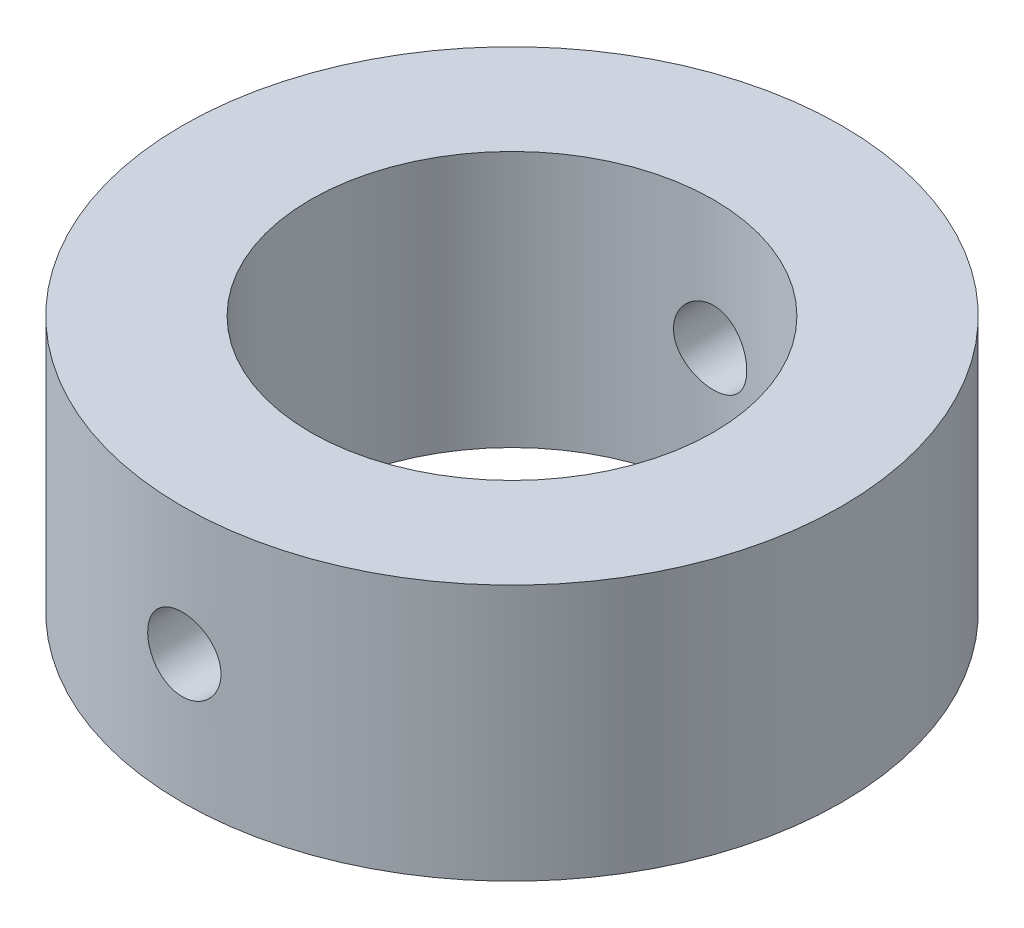
SolidWorks part; units mm, degrees
ref_plane "Front Plane" through (0, 0, 0) normal (0, 0, 1) x (1, 0, 0)
ref_plane "Top Plane" through (0, 0, 0) normal (0, 1, 0) x (1, 0, 0)
ref_plane "Right Plane" through (0, 0, 0) normal (1, 0, 0) x (0, 0, -1)
sketch "Sketch2" plane through (0, 0, 0) normal (0, 1, 0) x (1, 0, 0)
  circle A0 centre (0, 0) radius 18
  circle A1 centre (0, 0) radius 11
  dimension "D1" = 36
  dimension "D2" = 22
extrude "Boss-Extrude1" add sketch "Sketch2" along normal blind 14
sketch "Sketch3" plane through (0, 0, 0) normal (0, 0, 1) x (1, 0, 0)
  line L0 (0, 0) -> (0, 14) construction
  line L1 (11, 14) -> (-11, 14) construction
  circle A0 centre (0, 7) radius 2
  dimension "D1" = 4
extrude "Cut-Extrude1" cut sketch "Sketch3" against normal through all both and the other way through all
